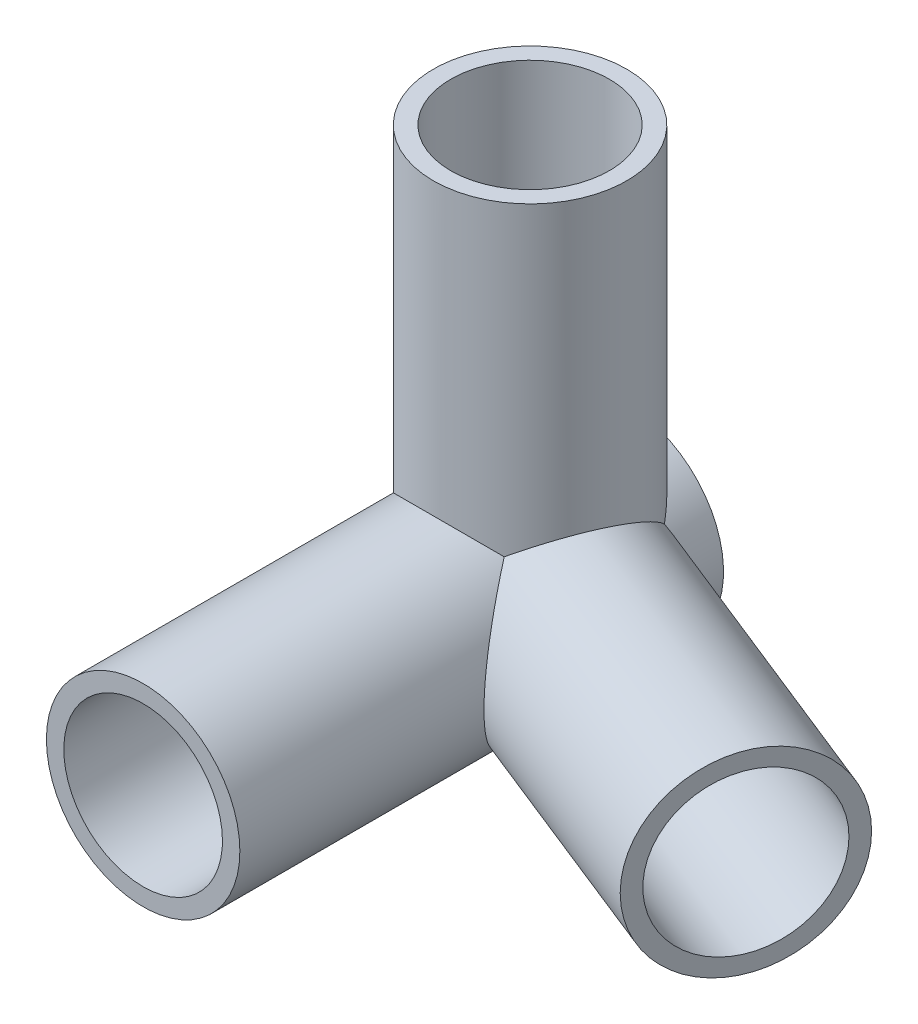
SolidWorks part; units mm, degrees
ref_plane "前视基准面" through (0, 0, 0) normal (0, 0, 1) x (1, 0, 0)
ref_plane "上视基准面" through (0, 0, 0) normal (0, 1, 0) x (1, 0, 0)
ref_plane "右视基准面" through (0, 0, 0) normal (1, 0, 0) x (0, 0, -1)
other "Configuration Table"
sketch "草图1" plane through (0, 0, 0) normal (0, 0, 1) x (1, 0, 0)
  line L3 (0, 0) -> (0, -260)
  line L4 (0, -260) -> (325.5646, -130)
  line L5 (325.5646, -130) -> (0, 0)
  circle A0 centre (0, 0) radius 4.1
  circle A1 centre (0, 0) radius 5
  point P2 (0, 0)
  dimension "D2" = 8.2
  dimension "D6" = 10
  dimension "D1" = 68.233
  dimension "D3" = 350.56
  dimension "D4" = 350.56
  dimension "D5" = 260
  dimension "D7" = 43.534
extrude "凸台-拉伸1" add sketch "草图1" along normal blind 25 contours L5 A1 L3 A0 | L3 A1 L5 A0
sketch "草图3" plane through (0, 0, 0) normal (0, 1, 0) x (1, 0, 0)
  circle A0 centre (0, -5) radius 5
  circle A1 centre (0, -5) radius 4.1
  dimension "D1" = 8.2
extrude "凸台-拉伸3" add sketch "草图3" along normal blind 20
sketch "草图4" plane through (0, 0, 0) normal (0, 1, 0) x (1, 0, 0)
  line L0 (0, 2.5893) -> (0, -24.2524) construction
  line L5 (0, -5) -> (18.5216, -12.3969) construction
  line L6 (0, -5) -> (1.8544, -0.3566)
  line L7 (1.8544, -0.3566) -> (20.428, -7.7742)
  line L8 (20.428, -7.7742) -> (18.5736, -12.4176)
  line L9 (0, -5) -> (18.5736, -12.4176)
  line L10 (0, -5) -> (18.5736, -12.4176)
  circle A4 centre (0, -5) radius 5 construction
  arc A5 (5, -5) -> (0, 0) centre (0, -5) ccw construction
  dimension "D1" = 68.23
  dimension "D2" = 20
revolve "旋转1" add sketch "草图4" angle 360 about L10
sketch "草图5" plane through (20.2958, 0, 8.1054) normal (0.9287, 0, 0.3709) x (0.3709, 0, -0.9287)
  circle A0 centre (-4.6434, 0) radius 4.1
  dimension "D1" = 8.2
extrude "切除-拉伸1" cut sketch "草图5" against normal blind 20
sketch "草图6" plane through (0, 0, 25) normal (0, 0, 1) x (1, 0, 0)
  circle A0 centre (0, 0) radius 4.1
extrude "切除-拉伸2" cut sketch "草图6" against normal blind 20
sketch "草图8" plane through (0, 20, 0) normal (0, 1, 0) x (1, 0, 0)
  circle A0 centre (0, -5) radius 4.1
extrude "切除-拉伸3" cut sketch "草图8" against normal blind 20
ref_plane "基准面1" through (0, 0, 10) normal (0, 0, 1) x (1, 0, 0)
sketch "草图10" plane through (0, 0, 10) normal (0, 0, 1) x (1, 0, 0)
  circle A0 centre (0, 0) radius 5
extrude "凸台-拉伸4" add sketch "草图10" along normal blind 2
ref_plane "基准面2" through (6.3656, 0, 2.5422) normal (0.9287, 0, 0.3709) x (0.3709, 0, -0.9287)
sketch "草图11" plane through (6.3656, 0, 2.5422) normal (0.9287, 0, 0.3709) x (0.3709, 0, -0.9287)
  circle A0 centre (-4.6434, 0) radius 5
extrude "凸台-拉伸5" add sketch "草图11" along normal blind 2
sketch "草图13" plane through (0, 0, 0) normal (0, 1, 0) x (1, 0, 0)
  circle A0 centre (0, -5) radius 5
ref_plane "基准面3" through (0, 5, 0) normal (0, 1, 0) x (1, 0, 0)
sketch "草图14" plane through (0, 5, 0) normal (0, 1, 0) x (1, 0, 0)
  circle A0 centre (0, -5) radius 5
extrude "凸台-拉伸7" add sketch "草图14" along normal blind 2
sketch "草图15" plane through (0, 0, 0) normal (0, 0, -1) x (-1, 0, 0)
  circle A0 centre (0, 0) radius 5
sketch "草图16" plane through (0, 0, 0) normal (0, 0, -1) x (-1, 0, 0)
  circle A0 centre (0, 0) radius 4.5336
extrude "凸台-拉伸10" add sketch "草图16" against normal blind 2
sketch "草图19" plane through (0, 7, 0) normal (0, 1, 0) x (1, 0, 0)
  circle A0 centre (0, -5) radius 4.1
extrude "凸台-拉伸11" add sketch "草图19" along normal blind 1
